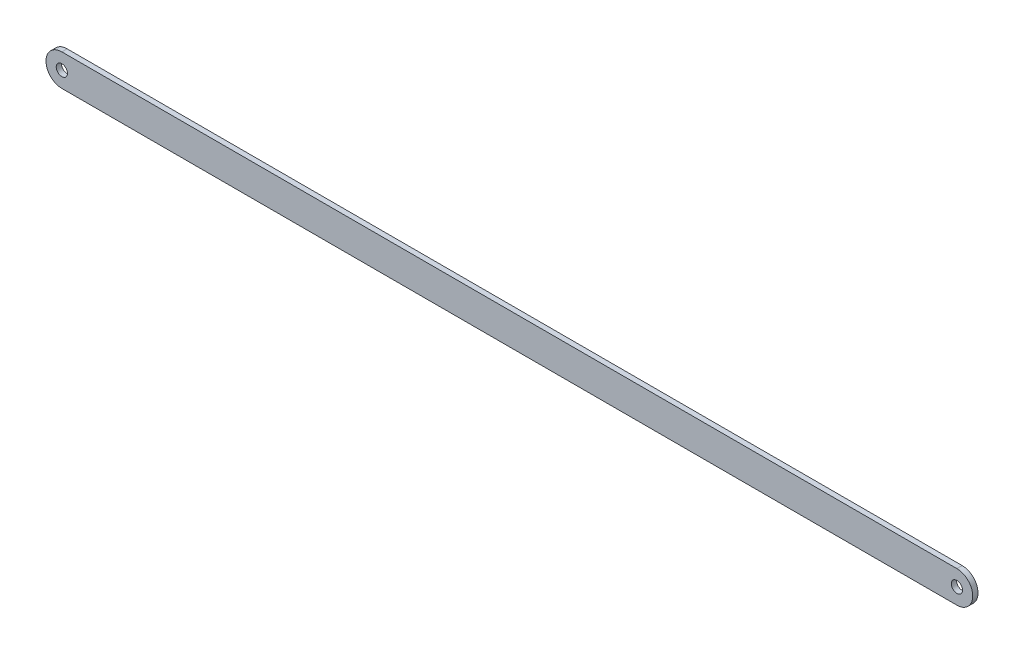
SolidWorks part; units mm, degrees
material "6063-O"
ref_plane "Front Plane" through (0, 0, 0) normal (0, 0, 1) x (1, 0, 0)
ref_plane "Top Plane" through (0, 0, 0) normal (0, 1, 0) x (1, 0, 0)
ref_plane "Right Plane" through (0, 0, 0) normal (1, 0, 0) x (0, 0, -1)
sketch "Sketch2" plane through (0, 0, 0) normal (0, 0, 1) x (1, 0, 0)
  line L0 (269.1082, 0) -> (-269.1082, 0) construction
  line L1 (1.7463, 0) -> (-1.7463, 0) construction
  line L2 (269.1082, -9.525) -> (-269.1082, -9.525)
  line L3 (269.1082, 9.525) -> (-269.1082, 9.525)
  line L4 (-269.1082, 0) -> (210.3719, -167.818) construction
  line L5 (210.3719, -167.818) -> (269.1082, 0) construction
  arc A0 (269.1082, -9.525) -> (269.1082, 9.525) centre (269.1082, 0) ccw
  arc A1 (-269.1082, 9.525) -> (-269.1082, -9.525) centre (-269.1082, 0) ccw
  point P5 (0, 0)
  dimension "D1" = 19.05
  dimension "D2" = 557.2664
  dimension "D3" = 508
  dimension "D4" = 177.8
extrude "Boss-Extrude1" add sketch "Sketch2" along normal mid plane 3.175
hole_wizard "1/4 Clearance Hole1" positions "Sketch4" profile "Sketch5" hole size "1/4" standard "ANSI Inch" end condition through all
sketch "Sketch4" plane through (0, 0, 1.5875) normal (0, 0, 1) x (1, 0, 0)
  point P0 (-269.1082, 0)
  point P3 (269.1082, 0)
sketch "Sketch5" plane through (-269.1082, 0, 1.5875) normal (1, 0, 0) x (0, -1, 0)
  line L0 (0, 0) -> (0, 3.175)
  line L1 (0, 3.175) -> (3.3782, 3.175)
  line L2 (3.3782, 3.175) -> (3.3782, 0)
  line L5 (3.3782, 0) -> (0, 0)
  line L11 (0, -6.35) -> (0, 107.95) construction
  dimension "Thru Hole Dia." = 6.7564
  dimension "Thru Hole Depth" = 3.175
